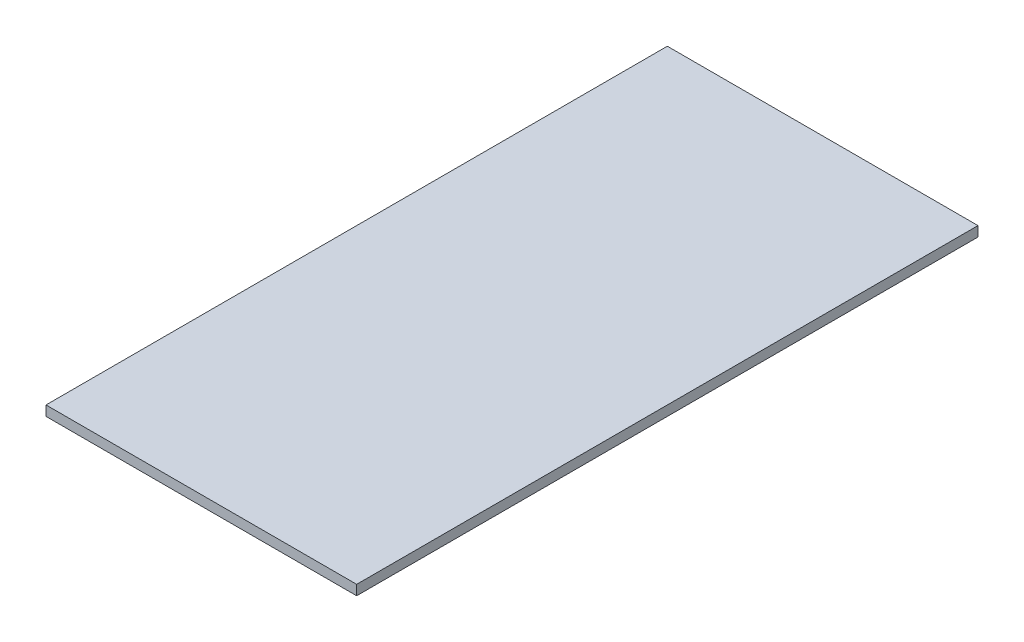
SolidWorks part; units mm, degrees
ref_plane "前视基准面" through (0, 0, 0) normal (0, 0, 1) x (1, 0, 0)
ref_plane "上视基准面" through (0, 0, 0) normal (0, 1, 0) x (1, 0, 0)
ref_plane "右视基准面" through (0, 0, 0) normal (1, 0, 0) x (0, 0, -1)
other "Configuration Table"
sketch "草图1" plane through (0, 0, 0) normal (0, 1, 0) x (1, 0, 0)
  line L1 (0, 0) -> (50, 0)
  line L2 (0, 0) -> (0, 100)
  line L3 (0, 100) -> (50, 100)
  line L4 (50, 0) -> (50, 100)
  line L5 (0, 0) -> (50, 100) construction
  line L6 (0, 100) -> (50, 0) construction
  point P4 (25, 50)
  dimension "D1" = 50
  dimension "D2" = 100
extrude "凸台-拉伸1" add sketch "草图1" along normal blind 1.6
